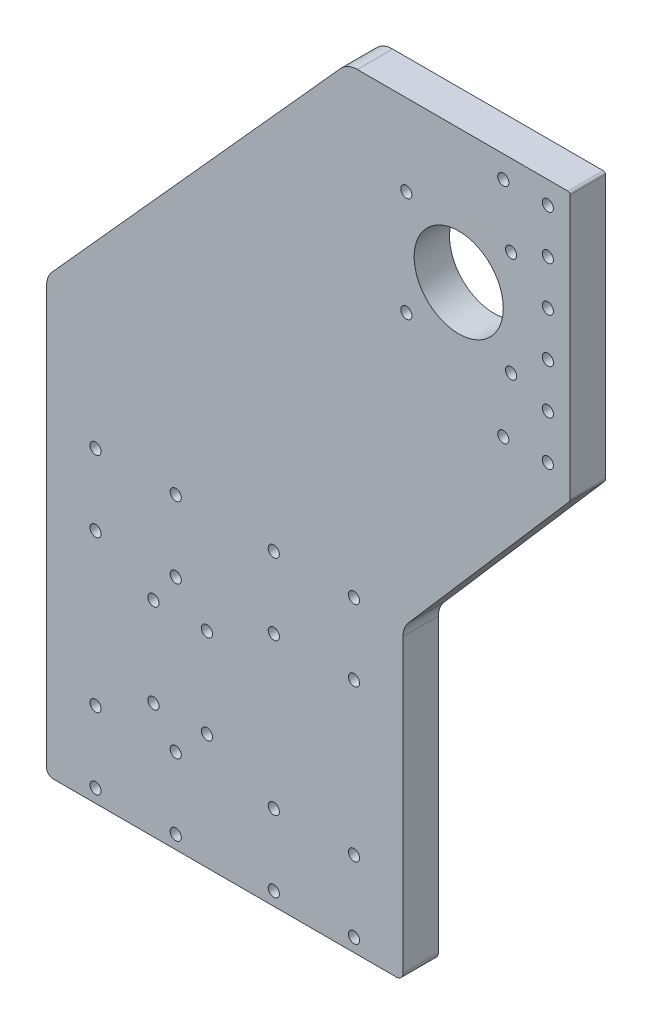
SolidWorks part; units mm, degrees
ref_plane "Front Plane" through (0, 0, 0) normal (0, 0, 1) x (1, 0, 0)
ref_plane "Top Plane" through (0, 0, 0) normal (0, 1, 0) x (1, 0, 0)
ref_plane "Right Plane" through (0, 0, 0) normal (1, 0, 0) x (0, 0, -1)
sketch "Sketch1" plane through (0, 0, 0) normal (0, 0, 1) x (1, 0, 0)
  line L0 (-80, 0) -> (80, 0) construction
  line L1 (-80, 72) -> (80, 72)
  line L2 (-80, 72) -> (-80, -72)
  line L3 (-80, -72) -> (80, -72)
  line L4 (80, 72) -> (80, -72)
  line L5 (-80, 72) -> (80, -72) construction
  line L6 (-80, -72) -> (80, 72) construction
  line L7 (0, 72) -> (0, -72) construction
  circle A0 centre (-58, -66) radius 2.5
  circle A1 centre (-22, -66) radius 2.5
  circle A2 centre (-58, -34) radius 2.5
  circle A3 centre (-22, -34) radius 2.5
  circle A4 centre (58, -66) radius 2.5
  circle A5 centre (22, -66) radius 2.5
  circle A6 centre (22, -34) radius 2.5
  circle A7 centre (58, -34) radius 2.5
  circle A8 centre (-58, 66) radius 2.5
  circle A9 centre (-22, 66) radius 2.5
  circle A10 centre (22, 66) radius 2.5
  circle A11 centre (58, 66) radius 2.5
  circle A12 centre (58, 34) radius 2.5
  circle A13 centre (22, 34) radius 2.5
  circle A14 centre (-22, 34) radius 2.5
  circle A15 centre (-58, 34) radius 2.5
  point P0 (0, 0)
  dimension "D3" = 5
  dimension "D4" = 5
  dimension "D5" = 5
  dimension "D6" = 5
  dimension "D7" = 36
  dimension "D8" = 32
  dimension "D9" = 80
  dimension "D10" = 100
  dimension "D1" = 144
  dimension "D2" = 160
extrude "Boss-Extrude1" add sketch "Sketch1" along normal blind 15.875
sketch "Sketch2" plane through (0, 0, 15.875) normal (0, 0, 1) x (1, 0, 0)
  line L1 (55, 272) -> (155, 272)
  line L2 (155, 272) -> (155, 152)
  line L3 (155, 152) -> (80, 152)
  line L4 (80, 152) -> (80, 72)
  line L5 (80, 72) -> (-80, 72)
  line L6 (-80, 72) -> (-80, 122)
  line L7 (-80, 122) -> (55, 272)
  dimension "D1" = 75
  dimension "D2" = 120
  dimension "D3" = 200
  dimension "D4" = 100
  dimension "D5" = 50
extrude "Boss-Extrude2" add sketch "Sketch2" against normal through all
sketch "Sketch3" plane through (0, 0, 15.875) normal (0, 0, 1) x (1, 0, 0)
  line L0 (155, 152) -> (80, 65.5898)
  line L1 (80, -72) -> (80, 152) construction
  line L2 (80, 65.5898) -> (80, 152)
  line L3 (80, 152) -> (155, 152)
  line L6 (80, -72) -> (80, 152) construction
extrude "Boss-Extrude3" add sketch "Sketch3" against normal through all
fillet "Fillet2" radius 10 3 edges at (80, 65.5898, 7.9375) (-80, 122, 7.9375) (55, 272, 7.9375)
sketch "Sketch4" plane through (0, 0, 15.875) normal (0, 0, 1) x (1, 0, 0)
  line L0 (-20, 0) -> (-20, 33.2415) construction
  line L1 (-20, 33.2415) -> (-20, 0) construction
  line L2 (-20, 0) -> (-37.74, 0) construction
  circle A0 centre (-32, 20) radius 2.5
  circle A1 centre (-8, 20) radius 2.5
  circle A2 centre (-8, -20) radius 2.5
  circle A3 centre (-32, -20) radius 2.5
  dimension "D3" = 5
  dimension "D1" = 20
  dimension "D2" = 12
  dimension "D4" = 20
extrude "Cut-Extrude1" cut sketch "Sketch4" against normal through all
fillet "Fillet3" radius 1 1 edges at (155, 272, 7.9375)
sketch "Sketch5" plane through (0, 0, 15.875) normal (0, 0, 1) x (1, 0, 0)
  line L0 (145, 120.8838) -> (145, 262) construction
  line L1 (145, 262) -> (23.5289, 262) construction
  line L2 (154, 272) -> (59.4536, 272) construction
  line L3 (155, 152) -> (155, 271) construction
  circle A0 centre (145, 262) radius 2.5
  circle A1 centre (145, 242) radius 2.5
  circle A2 centre (145, 222) radius 2.5
  circle A3 centre (145, 202) radius 2.5
  circle A4 centre (145, 182) radius 2.5
  circle A5 centre (145, 162) radius 2.5
  circle A6 centre (125, 162) radius 2.5
  circle A7 centre (125, 262) radius 2.5
  dimension "D3" = 5
  dimension "D1" = 10
  dimension "D2" = 10
  dimension "D4" = 6
  dimension "D5" = 2
extrude "Cut-Extrude2" cut sketch "Sketch5" against normal through all
fillet "Fillet4" radius 2 1 edges at (155, 152, 7.9375)
sketch "Sketch6" plane through (0, 0, 15.875) normal (0, 0, 1) x (1, 0, 0)
  line L0 (145, 222) -> (145, 202) construction
  line L1 (145, 202) -> (145, 212) construction
  line L2 (145, 212) -> (65, 212) construction
  line L3 (81.5, 212) -> (81.5, 235.5) construction
  circle A0 centre (105, 212) radius 20
  circle A1 centre (145, 222) radius 2.5 construction
  circle A2 centre (81.5, 235.5) radius 2.5
  circle A6 centre (128.5, 235.5) radius 2.5
  circle A7 centre (128.5, 188.5) radius 2.5
  circle A8 centre (81.5, 188.5) radius 2.5
  point P9 (105, 212)
  point P23 (90, 182)
  point P24 (105, 212)
  dimension "D1" = 40
  dimension "D2" = 40
  dimension "D5" = 5
  dimension "D3" = 23.5
  dimension "D4" = 23.5
  dimension "D6" = 4
extrude "Cut-Extrude3" cut sketch "Sketch6" against normal through all
fillet "Fillet5" radius 3 2 edges at (80, -72, 7.9375) (-80, -72, 7.9375)
